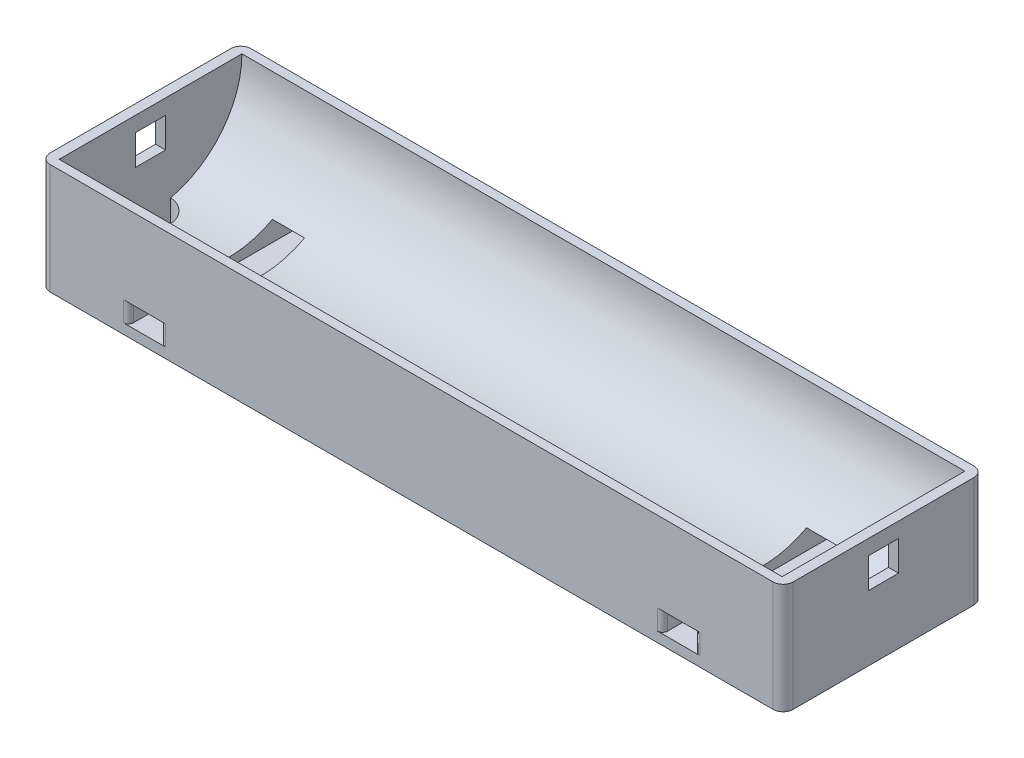
SolidWorks part; units mm, degrees
ref_plane "Plano frontal" through (0, 0, 0) normal (0, 0, 1) x (1, 0, 0)
ref_plane "Plano superior" through (0, 0, 0) normal (0, 1, 0) x (1, 0, 0)
ref_plane "Plano direito" through (0, 0, 0) normal (1, 0, 0) x (0, 0, -1)
sketch "Esboço1" plane through (0, 0, 0) normal (0, 1, 0) x (1, 0, 0)
  line L1 (-37, -10) -> (37, -10)
  line L2 (-37, -10) -> (-37, 10)
  line L3 (-37, 10) -> (37, 10)
  line L4 (37, -10) -> (37, 10)
  line L5 (-37, -10) -> (37, 10) construction
  line L6 (-37, 10) -> (37, -10) construction
  point P0 (0, 0)
  dimension "D1" = 20
  dimension "D2" = 74
extrude "Ressalto-extrusão1" add sketch "Esboço1" along normal blind 11
sketch "Esboço4" plane through (0, 11, 0) normal (0, 1, 0) x (1, 0, 0)
  line L0 (-36, 0) -> (36, 0)
  line L1 (-38.3361, 0) -> (38.4805, 0) construction
  line L3 (-36, 0) -> (36, 0)
  line L4 (-36, 0) -> (-36, -9.1)
  line L5 (-36, -9.1) -> (36, -9.1)
  line L6 (36, 0) -> (36, -9.1)
  point P4 (0, 0)
  dimension "D1" = 72
  dimension "D2" = 9.1
revolve "Corte-Revolução2" cut sketch "Esboço4" angle 360 about L1
sketch "Esboço5" plane through (-36, 0, 0) normal (1, 0, 0) x (0, 0, -1)
  line L0 (0, 11.8501) -> (0, -0.3681) construction
  line L1 (-1.5, 9.5) -> (1.5, 9.5)
  line L2 (-1.5, 9.5) -> (-1.5, 6.5)
  line L3 (-1.5, 6.5) -> (1.5, 6.5)
  line L4 (1.5, 9.5) -> (1.5, 6.5)
  line L5 (-1.5, 9.5) -> (1.5, 6.5) construction
  line L6 (-1.5, 6.5) -> (1.5, 9.5) construction
  line L7 (-9.1, 11) -> (9.1, 11) construction
  point P0 (0, 8)
  point P8 (0, 7.2165)
  point P9 (0, 5.8651)
  point P10 (0, 5.9478)
  dimension "D1" = 3
  dimension "D2" = 3
  dimension "D3" = 3
extrude "Corte-extrusão2" cut sketch "Esboço5" against normal blind 2.5
mirror "Espelhar1" about plane through (0, 0, 0) normal (1, 0, 0) of "Corte-extrusão2"
sketch "Esboço6" plane through (0, 0, 0) normal (0, 1, 0) x (1, 0, 0)
  line L0 (-36, -9.1) -> (-36, 9.1) construction
  line L1 (-36, 2) -> (-36, -2)
  arc A0 (-36, 2) -> (-36, -2) centre (-36, 0) cw
  dimension "D1" = 2
extrude "Corte-extrusão3" cut sketch "Esboço6" along normal through all
fillet "Filete1" radius 1 1 edges at (37, 5.5, 10)
fillet "Filete2" radius 1 1 edges at (37, 5.5, -10)
fillet "Filete3" radius 1 1 edges at (-37, 5.5, 10)
fillet "Filete4" radius 1 1 edges at (-37, 5.5, -10)
mirror "Espelhar2" about plane through (0, 0, 0) normal (1, 0, 0) of "Corte-extrusão3"
sketch "Esboço8" plane through (0, 0, 10) normal (0, 0, 1) x (1, 0, 0)
  line L0 (-35.7243, 2) -> (49.564, 2) construction
  line L1 (-36, 0) -> (36, 0) construction
  line L2 (0, 14.2832) -> (0, -3.4852) construction
  line L4 (-28.2, 1) -> (-25, 1)
  line L5 (-28.2, 1) -> (-28.2, 3)
  line L6 (-28.2, 3) -> (-25, 3)
  line L7 (-25, 1) -> (-25, 3)
  line L8 (-28.2, 1) -> (-25, 3) construction
  line L9 (-28.2, 3) -> (-25, 1) construction
  point P7 (-26.6, 2)
  dimension "D1" = 2
  dimension "D2" = 3.2
  dimension "D3" = 2
  dimension "D4" = 25
extrude "Corte-extrusão5" cut sketch "Esboço8" against normal through all
fillet "Filete5" radius 0.5 1 edges at (-28.2, 2, 10)
fillet "Filete6" radius 0.5 1 edges at (-25, 2, 10)
fillet "Filete7" radius 0.5 1 edges at (-25, 2, -10)
fillet "Filete8" radius 0.5 1 edges at (-28.2, 2, -10)
mirror "Espelhar3" about plane through (0, 0, 0) normal (1, 0, 0) of "Filete6", "Corte-extrusão5", "Filete5", "Filete7", "Filete8"
